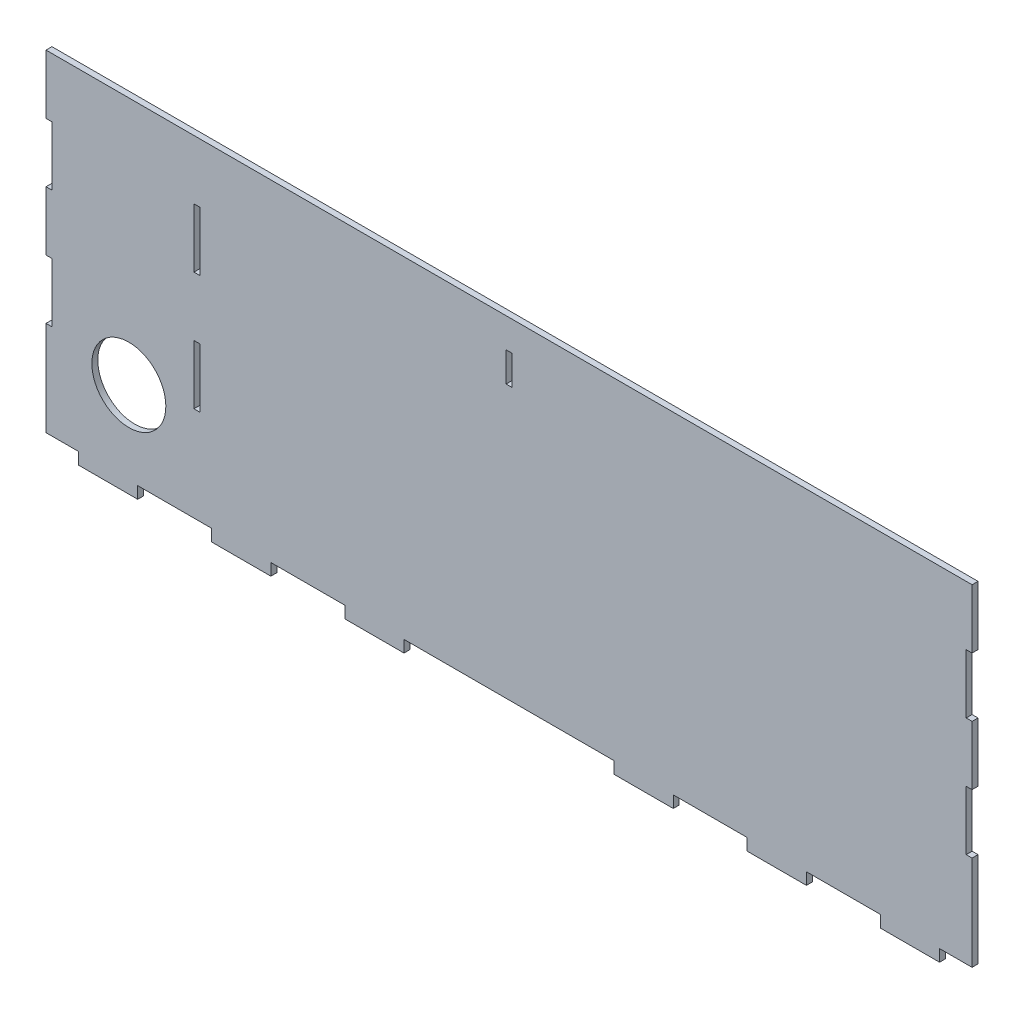
SolidWorks part; units mm, degrees
ref_plane "Front Plane" through (0, 0, 0) normal (0, 0, 1) x (1, 0, 0)
ref_plane "Top Plane" through (0, 0, 0) normal (0, 1, 0) x (1, 0, 0)
ref_plane "Right Plane" through (0, 0, 0) normal (1, 0, 0) x (0, 0, -1)
sketch "Sketch2" plane through (0, 0, 0) normal (0, 0, 1) x (1, 0, 0)
  line L0 (-100.5, -56) -> (-100.5, -60)
  line L1 (-156.5, 56) -> (-145.5, 56)
  line L2 (-156.5, 56) -> (-156.5, 36)
  line L3 (-156.5, -56) -> (-145.5, -56)
  line L4 (156.5, 56) -> (156.5, 36)
  line L5 (-156.5, 56) -> (156.5, -56) construction
  line L6 (-156.5, -56) -> (156.5, 56) construction
  line L8 (-145.5, -56) -> (-145.5, -60)
  line L9 (-145.5, -60) -> (-125.5, -60)
  line L10 (-125.5, -56) -> (-125.5, -60)
  line L12 (-80.5, -56) -> (-80.5, -60)
  line L13 (-100.5, -60) -> (-80.5, -60)
  line L14 (-55.5, -56) -> (-55.5, -60)
  line L16 (-35.5, -56) -> (-35.5, -60)
  line L17 (-55.5, -60) -> (-35.5, -60)
  line L18 (0, -55) -> (0, 55) construction
  line L19 (145.5, -60) -> (125.5, -60)
  line L20 (125.5, -56) -> (125.5, -60)
  line L22 (145.5, -56) -> (145.5, -60)
  line L24 (80.5, -56) -> (80.5, -60)
  line L25 (100.5, -60) -> (80.5, -60)
  line L26 (100.5, -56) -> (100.5, -60)
  line L28 (35.5, -56) -> (35.5, -60)
  line L29 (55.5, -60) -> (35.5, -60)
  line L30 (55.5, -56) -> (55.5, -60)
  line L31 (-125.5, -56) -> (-100.5, -56)
  line L32 (-80.5, -56) -> (-55.5, -56)
  line L33 (-35.5, -56) -> (35.5, -56)
  line L34 (145.5, -56) -> (156.5, -56)
  line L35 (100.5, -56) -> (125.5, -56)
  line L36 (55.5, -56) -> (80.5, -56)
  line L38 (-156.5, 36) -> (-154.5, 36)
  line L40 (-156.5, 16) -> (-154.5, 16)
  line L41 (-154.5, 36) -> (-154.5, 16)
  line L42 (-156.5, -4) -> (-154.5, -4)
  line L43 (-154.5, -4) -> (-154.5, -24)
  line L44 (-156.5, -24) -> (-154.5, -24)
  line L45 (156.5, -4) -> (154.5, -4)
  line L46 (154.5, -4) -> (154.5, -24)
  line L47 (156.5, -24) -> (154.5, -24)
  line L49 (156.5, 16) -> (154.5, 16)
  line L50 (154.5, 36) -> (154.5, 16)
  line L51 (156.5, 36) -> (154.5, 36)
  line L53 (-156.5, 16) -> (-156.5, -4)
  line L54 (-156.5, -24) -> (-156.5, -56)
  line L55 (156.5, 16) -> (156.5, -4)
  line L56 (156.5, -24) -> (156.5, -56)
  line L57 (-145.5, 58) -> (-125.5, 58)
  line L62 (-100.5, 58) -> (-80.5, 58)
  line L63 (-106.5, 36) -> (-104.5, 36)
  line L64 (-106.5, 36) -> (-106.5, 16)
  line L65 (-106.5, 16) -> (-104.5, 16)
  line L66 (-104.5, 36) -> (-104.5, 16)
  line L67 (-106.5, -4) -> (-106.5, -24)
  line L68 (-106.5, -4) -> (-104.5, -4)
  line L69 (-104.5, -4) -> (-104.5, -24)
  line L70 (-106.5, -24) -> (-104.5, -24)
  line L71 (-55.5, 58) -> (-35.5, 58)
  line L72 (55.5, 58) -> (35.5, 58)
  line L73 (100.5, 58) -> (80.5, 58)
  line L74 (145.5, 58) -> (125.5, 58)
  line L75 (-145.5, 58) -> (-145.5, 56)
  line L76 (-125.5, 58) -> (-125.5, 56)
  line L77 (-100.5, 58) -> (-100.5, 56)
  line L78 (-80.5, 58) -> (-80.5, 56)
  line L79 (-55.5, 58) -> (-55.5, 56)
  line L80 (-35.5, 58) -> (-35.5, 56)
  line L81 (35.5, 58) -> (35.5, 56)
  line L82 (55.5, 58) -> (55.5, 56)
  line L83 (80.5, 58) -> (80.5, 56)
  line L84 (100.5, 58) -> (100.5, 56)
  line L85 (145.5, 58) -> (145.5, 56)
  line L86 (125.5, 58) -> (125.5, 56)
  line L87 (145.5, 56) -> (156.5, 56)
  line L88 (100.5, 56) -> (125.5, 56)
  line L89 (55.5, 56) -> (80.5, 56)
  line L90 (-35.5, 56) -> (35.5, 56)
  line L91 (-80.5, 56) -> (-55.5, 56)
  line L92 (-125.5, 56) -> (-100.5, 56)
  circle A0 centre (-128.5, -28) radius 12.5
  point P0 (0, 0)
  dimension "D3" = 25
  dimension "D1" = 313
  dimension "D2" = 112
  dimension "D4" = 28
  dimension "D5" = 28
  dimension "D6" = 4
  dimension "D7" = 11
  dimension "D8" = 20
  dimension "D10" = 25
  dimension "D11" = 20
  dimension "D12" = 2
  dimension "D13" = 20
  dimension "D15" = 20
  dimension "D16" = 2
  dimension "D17" = 20
  dimension "D18" = 20
  dimension "D19" = 50
  dimension "D21" = 20
  dimension "D23" = 2
  dimension "D9" = 3
  dimension "D14" = 2
  dimension "D20" = 2
  dimension "D22" = 2
extrude "Boss-Extrude1" add sketch "Sketch2" along normal blind 2
sketch "Sketch3" plane through (0, 0, 2) normal (0, 0, 1) x (1, 0, 0)
  line L1 (-145.5, 58) -> (-125.5, 58)
  line L2 (-145.5, 58) -> (-145.5, 56)
  line L3 (-145.5, 56) -> (-125.5, 56)
  line L4 (-125.5, 58) -> (-125.5, 56)
  line L5 (-100.5, 58) -> (-80.5, 58)
  line L6 (-100.5, 58) -> (-100.5, 56)
  line L7 (-100.5, 56) -> (-80.5, 56)
  line L8 (-80.5, 58) -> (-80.5, 56)
  line L9 (-55.5, 58) -> (-35.5, 58)
  line L10 (-55.5, 58) -> (-55.5, 56)
  line L11 (-55.5, 56) -> (-35.5, 56)
  line L12 (-35.5, 58) -> (-35.5, 56)
  line L13 (35.5, 58) -> (55.5, 58)
  line L14 (35.5, 58) -> (35.5, 56)
  line L15 (35.5, 56) -> (55.5, 56)
  line L16 (55.5, 58) -> (55.5, 56)
  line L17 (80.5, 58) -> (100.5, 58)
  line L18 (80.5, 58) -> (80.5, 56)
  line L19 (80.5, 56) -> (100.5, 56)
  line L20 (100.5, 58) -> (100.5, 56)
  line L21 (125.5, 58) -> (145.5, 58)
  line L22 (125.5, 58) -> (125.5, 56)
  line L23 (125.5, 56) -> (145.5, 56)
  line L24 (145.5, 58) -> (145.5, 56)
extrude "Cut-Extrude1" cut sketch "Sketch3" against normal through all both and the other way through all
sketch "Sketch5" plane through (0, 0, 2) normal (0, 0, 1) x (1, 0, 0)
  line L0 (-154.5, 36) -> (-154.5, 16) construction
  line L1 (-1, 46) -> (1, 46)
  line L2 (-1, 46) -> (-1, 36)
  line L3 (-1, 36) -> (1, 36)
  line L4 (1, 46) -> (1, 36)
  line L5 (-1, 46) -> (1, 36) construction
  line L6 (-1, 36) -> (1, 46) construction
  line L7 (156.5, 56) -> (-156.5, 56) construction
  point P0 (0, 41)
  dimension "D1" = 155.5
  dimension "D2" = 2
  dimension "D3" = 10
  dimension "D4" = 10
extrude "Cut-Extrude2" cut sketch "Sketch5" against normal through all both and the other way through all
